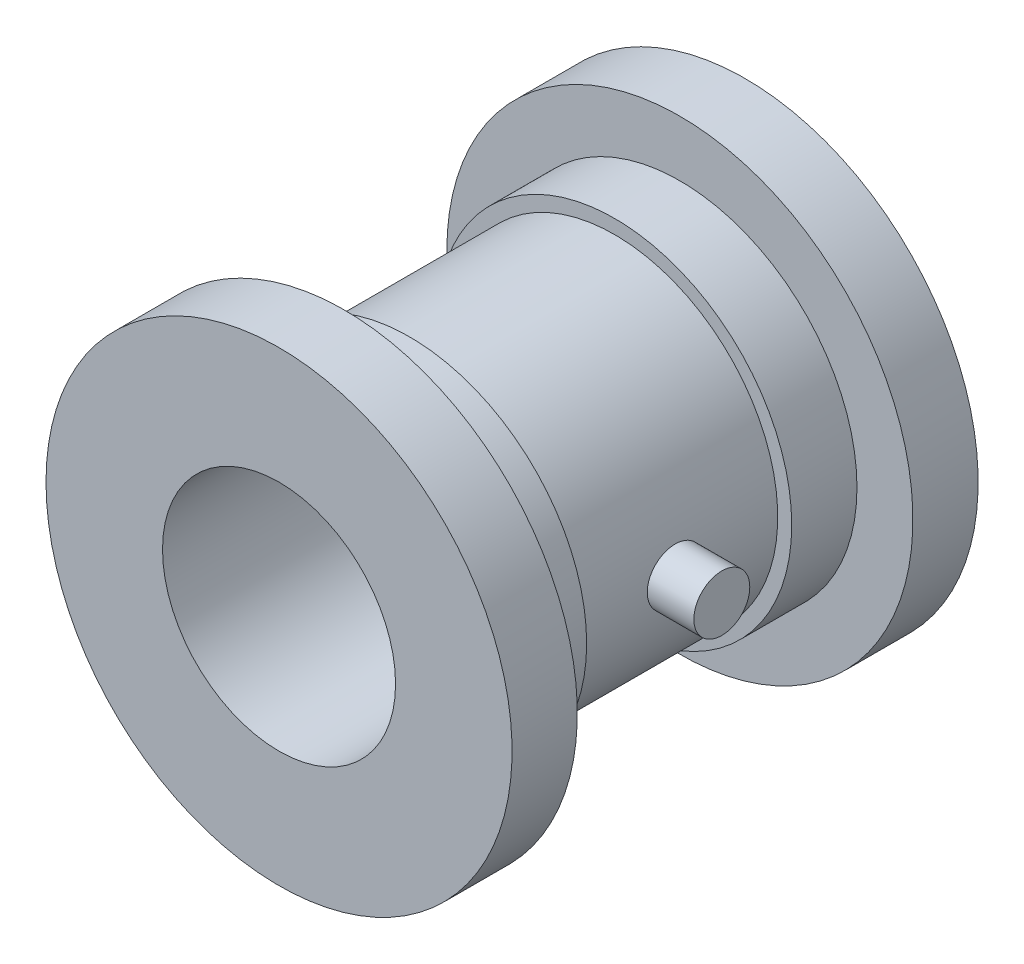
SolidWorks part; units mm, degrees
ref_plane "Front Plane" through (0, 0, 0) normal (0, 0, 1) x (1, 0, 0)
ref_plane "Top Plane" through (0, 0, 0) normal (0, 1, 0) x (1, 0, 0)
ref_plane "Right Plane" through (0, 0, 0) normal (1, 0, 0) x (0, 0, -1)
sketch "Sketch1" plane through (0, 0, 0) normal (1, 0, 0) x (0, 0, -1)
  line L0 (-11, 19) -> (-11, 17.5)
  line L1 (158.6794, 0) -> (-166.8168, 0) construction
  line L2 (0, 0) -> (0, -113.7542) construction
  line L3 (0, -113.7542) -> (0, 12.5) construction
  line L4 (-25, 12.5) -> (25, 12.5)
  line L5 (25, 12.5) -> (25, 25)
  line L6 (0, 17.5) -> (0, 93.4106) construction
  line L7 (-18, 19) -> (-11, 19)
  line L8 (25, 25) -> (18, 25)
  line L9 (18, 25) -> (18, 19)
  line L10 (18, 19) -> (11, 19)
  line L11 (11, 19) -> (11, 17.5)
  line L12 (11, 17.5) -> (-11, 17.5)
  line L13 (-18, 25) -> (-18, 19)
  line L14 (-25, 25) -> (-18, 25)
  line L15 (-25, 12.5) -> (-25, 25)
revolve "Revolve1" add sketch "Sketch1" angle 360 about L1
sketch "Sketch2" plane through (0, 0, 0) normal (1, 0, 0) x (0, 0, -1)
  circle A0 centre (0, 0) radius 2
extrude "Cut-Extrude2" cut sketch "Sketch2" against normal blind 78
ref_plane "Plane1" through (17.5, 0, 0) normal (1, 0, 0) x (0, 0, -1)
sketch "Sketch3" plane through (17.5, 0, 0) normal (1, 0, 0) x (0, 0, -1)
  circle A0 centre (0, 0) radius 3
extrude "Boss-Extrude1" add sketch "Sketch3" along normal blind 5 separate body
